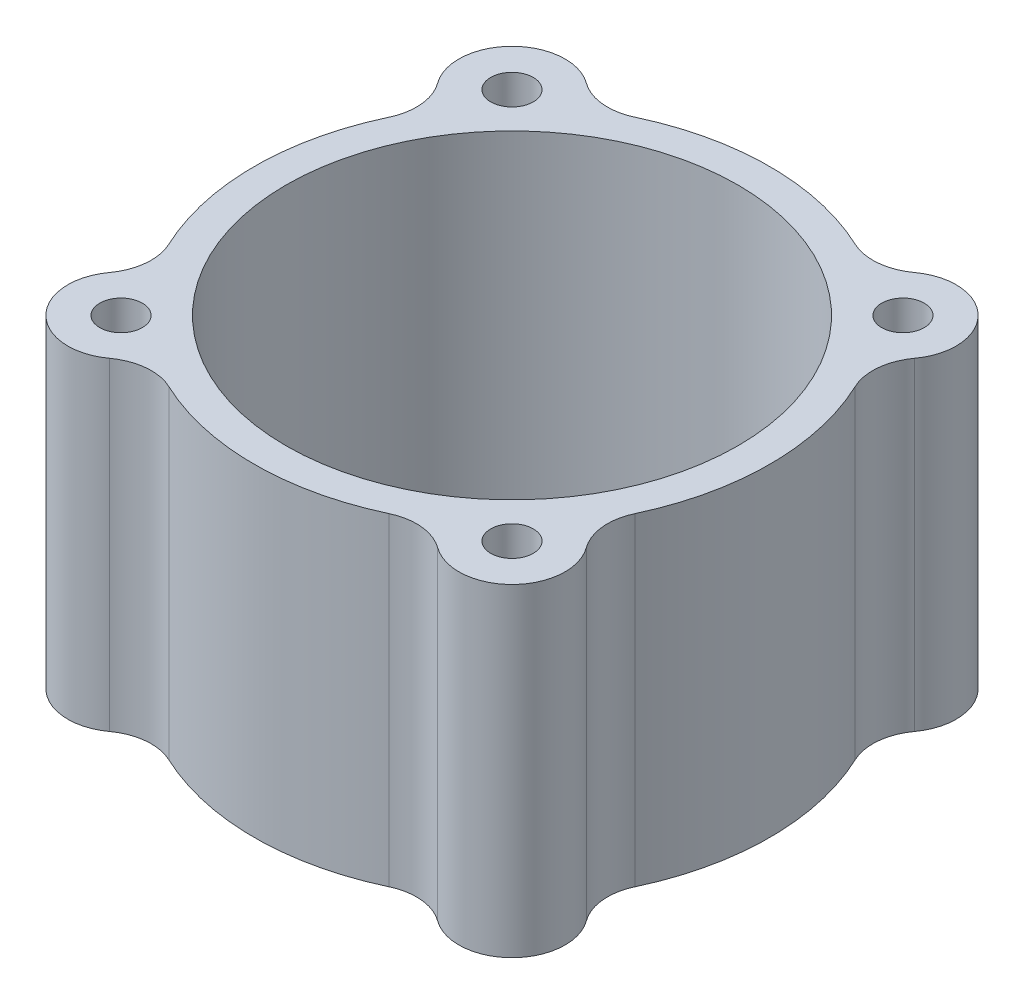
SolidWorks part; units mm, degrees
ref_plane "Front Plane" through (0, 0, 0) normal (0, 0, 1) x (1, 0, 0)
ref_plane "Top Plane" through (0, 0, 0) normal (0, 1, 0) x (1, 0, 0)
ref_plane "Right Plane" through (0, 0, 0) normal (1, 0, 0) x (0, 0, -1)
sketch "Sketch1" plane through (0, 0, 0) normal (0, 1, 0) x (1, 0, 0)
  circle A0 centre (0, 0) radius 21.25
  circle A1 centre (-18.3848, 18.3848) radius 2
  arc A2 (-15.4318, 22.4196) -> (-22.4196, 15.4318) centre (-18.3848, 18.3848) ccw
  arc A3 (-15.4318, 22.4196) -> (-10.3457, 21.9324) centre (-12.4789, 26.4545) ccw
  arc A4 (-22.4196, 15.4318) -> (-21.9324, 10.3457) centre (-26.4545, 12.4789) cw
  circle A5 centre (18.3848, 18.3848) radius 2
  arc A6 (22.4196, 15.4318) -> (15.4318, 22.4196) centre (18.3848, 18.3848) ccw
  arc A7 (22.4196, 15.4318) -> (21.9324, 10.3457) centre (26.4545, 12.4789) ccw
  arc A8 (15.4318, 22.4196) -> (10.3457, 21.9324) centre (12.4789, 26.4545) cw
  arc A9 (21.9324, -10.3457) -> (21.9324, 10.3457) centre (0, 0) ccw
  circle A10 centre (18.3848, -18.3848) radius 2
  arc A11 (10.3457, 21.9324) -> (-10.3457, 21.9324) centre (0, 0) ccw
  arc A12 (15.4318, -22.4196) -> (22.4196, -15.4318) centre (18.3848, -18.3848) ccw
  arc A13 (15.4318, -22.4196) -> (10.3457, -21.9324) centre (12.4789, -26.4545) ccw
  arc A14 (22.4196, -15.4318) -> (21.9324, -10.3457) centre (26.4545, -12.4789) cw
  arc A15 (-10.3457, -21.9324) -> (10.3457, -21.9324) centre (0, 0) ccw
  circle A16 centre (-18.3848, -18.3848) radius 2
  arc A17 (-22.4196, -15.4318) -> (-15.4318, -22.4196) centre (-18.3848, -18.3848) ccw
  arc A18 (-22.4196, -15.4318) -> (-21.9324, -10.3457) centre (-26.4545, -12.4789) ccw
  arc A19 (-15.4318, -22.4196) -> (-10.3457, -21.9324) centre (-12.4789, -26.4545) cw
  arc A20 (-21.9324, 10.3457) -> (-21.9324, -10.3457) centre (0, 0) ccw
  circle A21 centre (0, 0) radius 26 construction
  point P35 (0, 0)
  dimension "D1" = 42.5
  dimension "D2" = 52
  dimension "D3" = 4
  dimension "D4" = 5
  dimension "D6" = 5
extrude "Boss-Extrude1" add sketch "Sketch1" along normal blind 30.4
